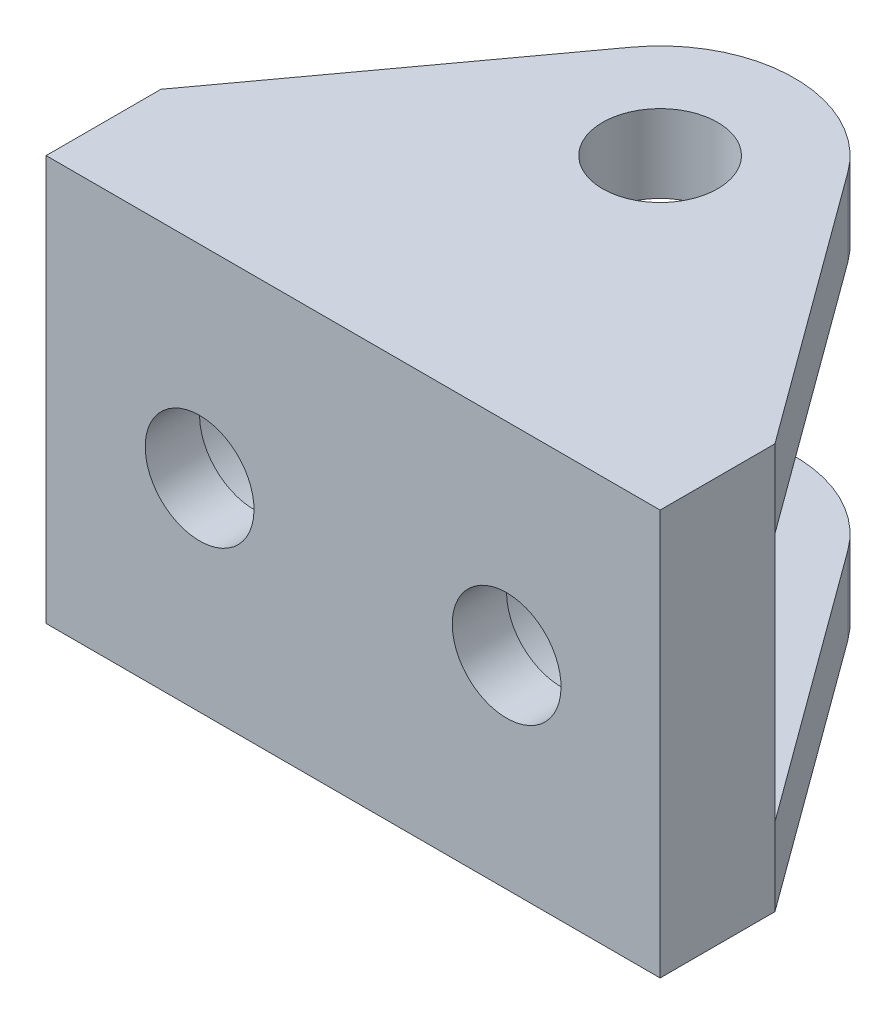
SolidWorks part; units mm, degrees
ref_plane "Front Plane" through (0, 0, 0) normal (0, 0, 1) x (1, 0, 0)
ref_plane "Top Plane" through (0, 0, 0) normal (0, 1, 0) x (1, 0, 0)
ref_plane "Right Plane" through (0, 0, 0) normal (1, 0, 0) x (0, 0, -1)
sketch "Sketch1" plane through (0, 0, 0) normal (0, 1, 0) x (1, 0, 0)
  line L0 (0, 0) -> (50.8, 0)
  line L1 (50.8, 0) -> (50.8, 9.4996)
  line L2 (0, 0) -> (0, 9.4996)
  line L3 (50.8, 9.4996) -> (34.3689, 31.961)
  line L4 (0, 9.4996) -> (16.4311, 31.961)
  line L5 (25.4, 0) -> (25.4, 43.8119) construction
  circle A0 centre (25.4, 25.4) radius 4.7625
  arc A1 (34.3689, 31.961) -> (16.4311, 31.961) centre (25.4, 25.4) ccw
  point P6 (19.0885, 29.8991)
  point P7 (50.7139, 6.5425)
  point P13 (35.3611, 29.3255)
  dimension "D4" = 6.35
  dimension "D5" = 9.525
  dimension "D1" = 25.4
  dimension "D2" = 50.8
  dimension "D3" = 9.4996
extrude "Boss-Extrude1" add sketch "Sketch1" along normal blind 33.528
sketch "Sketch2" plane through (50.8, 0, 0) normal (1, 0, 0) x (0, 0, -1)
  line L0 (9.4996, 16.764) -> (9.4996, 27.0891)
  line L1 (9.4996, 33.528) -> (9.4996, 0) construction
  line L2 (9.4996, 27.0891) -> (41.2496, 27.0891)
  line L3 (9.4996, 16.764) -> (9.4996, 6.4389)
  line L4 (9.4996, 6.4389) -> (41.2496, 6.4389)
  line L5 (41.2496, 6.4389) -> (41.2496, 27.0891)
  point P4 (0, 0)
  point P9 (40.9955, 22.1299)
  dimension "D1" = 20.6502
  dimension "D2" = 31.75
extrude "Cut-Extrude1" cut sketch "Sketch2" against normal through all
sketch "Sketch3" plane through (0, 0, -9.4996) normal (0, 0, -1) x (-1, 0, 0)
  line L0 (-50.8, 16.764) -> (0, 16.764) construction
  line L1 (-50.8, 27.0891) -> (-50.8, 6.4389) construction
  line L2 (0, 27.0891) -> (0, 6.4389) construction
  line L3 (-25.4, 16.764) -> (-25.4, 27.0891) construction
  line L4 (0, 27.0891) -> (-50.8, 27.0891) construction
  point P10 (-38.1, 16.764)
  point P11 (-12.7, 16.764)
  dimension "D1" = 12.7
  dimension "D2" = 25.4
hole_wizard "CBORE for M8 Hex Head Bolt1" positions "Sketch3" profile "Sketch4" counterbore size "M8" standard "ANSI Metric" end condition through all
sketch "Sketch4" plane through (12.7, 16.764, -9.4996) normal (1, 0, 0) x (0, 1, 0)
  line L0 (0, 0) -> (0, 9.4996)
  line L1 (0, 9.4996) -> (4.5, 9.4996)
  line L3 (4.5, 9.4996) -> (4.5, 5)
  line L4 (4.5, 5) -> (8, 5)
  line L5 (8, 5) -> (8, 0)
  line L7 (8, 0) -> (0, 0)
  line L11 (0, -6.35) -> (0, 107.95) construction
  dimension "Thru Hole Dia." = 9
  dimension "Thru Hole Depth" = 9.4996
  dimension "C'Bore Dia." = 16
  dimension "C'Bore Depth" = 5
equation "\"1inch\"=62.1211"
